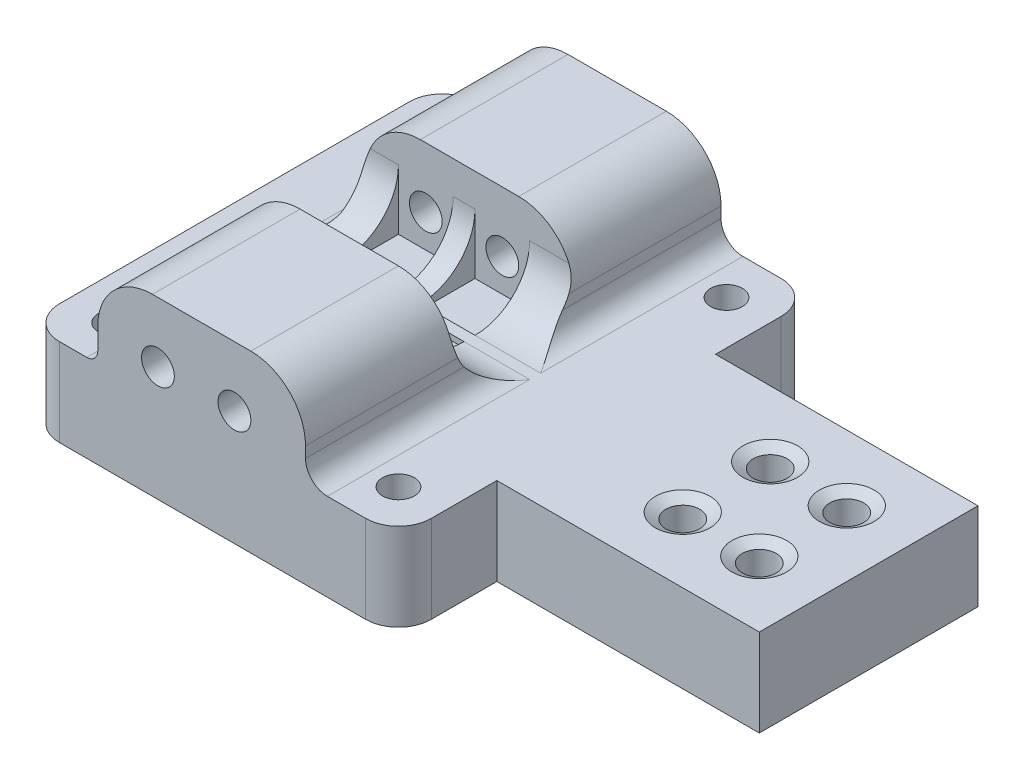
SolidWorks part; units mm, degrees
ref_plane "Front" through (0, 0, 0) normal (0, 0, 1) x (1, 0, 0)
ref_plane "Top" through (0, 0, 0) normal (0, 1, 0) x (1, 0, 0)
ref_plane "Right" through (0, 0, 0) normal (1, 0, 0) x (0, 0, -1)
sketch "Sketch1" plane through (0, 0, 0) normal (0, 1, 0) x (1, 0, 0)
  line L1 (0, 0) -> (300, 0)
  line L2 (0, 0) -> (0, -20)
  line L3 (0, -20) -> (300, -20)
  line L4 (300, 0) -> (300, -20)
  dimension "D1" = 20
  dimension "D2" = 300
extrude "Boss-Extrude1" add sketch "Sketch1" along normal blind 8
sketch "Sketch2" plane through (0, 0, 20) normal (0, 0, 1) x (1, 0, 0)
  line L0 (0, 8) -> (300, 8) construction
  line L1 (0, 0) -> (34, 0)
  line L2 (0, 0) -> (0, 8)
  line L3 (0, 8) -> (34, 8)
  line L4 (34, 0) -> (34, 8)
  line L5 (266, 8) -> (300, 8)
  line L6 (300, 0) -> (300, 8)
  line L7 (266, 0) -> (300, 0)
  line L8 (266, 0) -> (266, 8)
  dimension "D1" = 34
  dimension "D2" = 2
extrude "Boss-Extrude2" add sketch "Sketch2" along normal blind 9
sketch "Sketch3" plane through (0, 0, 0) normal (0, 0, -1) x (-1, 0, 0)
  line L0 (-300, 8) -> (0, 8) construction
  line L1 (0, 0) -> (-34, 0)
  line L2 (0, 0) -> (0, 8)
  line L3 (0, 8) -> (-34, 8)
  line L4 (-34, 0) -> (-34, 8)
  line L5 (-300, 0) -> (-300, 8)
  line L6 (-266, 8) -> (-300, 8)
  line L7 (-266, 0) -> (-266, 8)
  line L8 (-266, 0) -> (-300, 0)
  dimension "D1" = 34
  dimension "D2" = 2
extrude "Boss-Extrude3" add sketch "Sketch3" along normal blind 9
sketch "Sketch4" plane through (0, 8, 0) normal (0, 1, 0) x (1, 0, 0)
  line L0 (0, 9) -> (34, 9) construction
  line L1 (0, 9) -> (0, -29) construction
  circle A0 centre (4, 5) radius 1.45
  circle A1 centre (30, 5) radius 1.45
  circle A2 centre (30, -25) radius 1.45
  circle A3 centre (4, -25) radius 1.45
  circle A4 centre (296, -25) radius 1.45
  circle A5 centre (296, 5) radius 1.45
  circle A6 centre (270, -25) radius 1.45
  circle A7 centre (270, 5) radius 1.45
  dimension "D1" = 2.9
  dimension "D2" = 4
  dimension "D3" = 4
  dimension "D4" = 2
  dimension "D5" = 2
  dimension "D6" = 2
extrude "Cut-Extrude1" cut sketch "Sketch4" against normal through all
sketch "Sketch5" plane through (0, 0, 20) normal (0, 0, 1) x (1, 0, 0)
  line L0 (34, 8) -> (266, 8) construction
  line L1 (266, 0) -> (241, 0)
  line L2 (266, 0) -> (266, 8)
  line L3 (266, 8) -> (241, 8)
  line L4 (241, 0) -> (241, 8)
  dimension "D1" = 25
extrude "Boss-Extrude4" add sketch "Sketch5" along normal blind 17
sketch "Sketch6" plane through (0, 0, 0) normal (0, 0, -1) x (-1, 0, 0)
  line L0 (-266, 0) -> (-34, 0) construction
  line L1 (-266, 8) -> (-241, 8)
  line L2 (-266, 8) -> (-266, 0)
  line L3 (-266, 0) -> (-241, 0)
  line L4 (-241, 8) -> (-241, 0)
  dimension "D1" = 25
extrude "Boss-Extrude5" add sketch "Sketch6" along normal blind 17
sketch "Sketch12" plane through (0, 0, 37) normal (0, 0, 1) x (1, 0, 0)
  line L0 (241, 0) -> (266, 0) construction
  line L1 (241, 8) -> (249, 8)
  line L2 (241, 8) -> (241, 0)
  line L3 (241, 0) -> (249, 0)
  line L4 (249, 8) -> (249, 0)
  dimension "D1" = 8
extrude "Boss-Extrude7" add sketch "Sketch12" along normal blind 17
sketch "Sketch14" plane through (0, 0, 29) normal (0, 0, 1) x (1, 0, 0)
  line L0 (300, 8) -> (266, 8) construction
  line L1 (294.975, 8) -> (275, 8)
  line L2 (294.975, 8) -> (294.975, -5)
  line L3 (294.975, -5) -> (275, -4)
  line L4 (275, 8) -> (275, -4)
  line L7 (266, 8) -> (266, 0) construction
  dimension "D1" = 20
  dimension "D2" = 9
  dimension "D3" = 13
  dimension "D4" = 12
extrude "Boss-Extrude8" add sketch "Sketch14" along normal blind 12
sketch "Sketch15" plane through (294.975, 0, 0) normal (1, 0, 0) x (0, 0, -1)
  line L0 (-41, -5) -> (-41, 8) construction
  line L2 (-41, -5) -> (-29, -5) construction
  circle A0 centre (-35, 0) radius 1.6
  dimension "D1" = 3.2
  dimension "D2" = 6
  dimension "D3" = 5
extrude "Cut-Extrude7" cut sketch "Sketch15" against normal blind 20
sketch "Sketch16" plane through (0, 0, -9) normal (0, 0, -1) x (-1, 0, 0)
  line L0 (-266, 8) -> (-300, 8) construction
  line L1 (-295, 8) -> (-275, 8)
  line L2 (-295, 8) -> (-295, -5)
  line L3 (-295, -5) -> (-275, -5)
  line L4 (-275, 8) -> (-275, -5)
  line L6 (-266, 0) -> (-266, 8) construction
  dimension "D1" = 20
  dimension "D2" = 9
  dimension "D3" = 13
extrude "Boss-Extrude9" add sketch "Sketch16" along normal blind 12
sketch "Sketch17" plane through (295, 0, 0) normal (1, 0, 0) x (0, 0, -1)
  line L0 (21, -5) -> (9, -5) construction
  line L1 (21, 8) -> (21, -5) construction
  circle A0 centre (15, 0) radius 1.6
  dimension "D1" = 3.2
  dimension "D2" = 5
  dimension "D3" = 6
extrude "Cut-Extrude8" cut sketch "Sketch17" against normal blind 20
sketch "Sketch22" plane through (0, 8, 0) normal (0, 1, 0) x (1, 0, 0)
  line L0 (241, 17) -> (241, 0) construction
  line L1 (259, 9) -> (249, 9)
  line L2 (259, 9) -> (259, -29)
  line L3 (259, -29) -> (249, -29)
  line L4 (249, 9) -> (249, -29)
  line L5 (241, 17) -> (266, 17) construction
  line L6 (266, -37) -> (249, -37) construction
  dimension "D1" = 8
  dimension "D2" = 10
  dimension "D3" = 8
  dimension "D4" = 8
extrude "Cut-Extrude11" cut sketch "Sketch22" against normal through all
sketch "Sketch23" plane through (0, 0, 0) normal (0, -1, 0) x (-1, 0, 0)
  line L0 (-259, -29) -> (-259, 9) construction
  line L1 (-259, -19) -> (-267, -19)
  line L2 (-259, -19) -> (-259, -1)
  line L3 (-259, -1) -> (-267, -1)
  line L4 (-267, -19) -> (-267, -1)
  line L5 (-249, -29) -> (-259, -29) construction
  dimension "D1" = 8
  dimension "D2" = 10
  dimension "D3" = 10
extrude "Cut-Extrude12" cut sketch "Sketch23" against normal blind 4
sketch "Sketch24" plane through (259, 0, 0) normal (-1, 0, 0) x (0, 0, 1)
  line L0 (-9, 0) -> (-9, 8)
  line L1 (-9, 8) -> (-1, 8)
  line L2 (29, 8) -> (-9, 8) construction
  line L3 (-1, 8) -> (-9, 0)
  line L4 (29, 0) -> (29, 8)
  line L5 (29, 8) -> (21, 8)
  line L6 (21, 8) -> (29, 0)
  dimension "D1" = 8
  dimension "D2" = 8
extrude "Boss-Extrude12" add sketch "Sketch24" along normal blind 10
sketch "Sketch25" plane through (267, 0, 0) normal (-1, 0, 0) x (0, 0, 1)
  line L0 (19, 0) -> (19, 4)
  line L1 (19, 4) -> (15, 4)
  line L2 (1, 4) -> (19, 4) construction
  line L3 (15, 4) -> (19, 0)
  line L4 (1, 4) -> (5, 4)
  line L5 (5, 4) -> (1, 0)
  line L6 (1, 0) -> (1, 4)
  dimension "D1" = 4
  dimension "D2" = 4
extrude "Boss-Extrude13" add sketch "Sketch25" along normal blind 8
sketch "Sketch26" plane through (0, 8, 0) normal (0, 1, 0) x (1, 0, 0)
  line L0 (249, 1) -> (249, -21) construction
  line L1 (241, -54) -> (249, -54)
  line L2 (241, -54) -> (241, -6)
  line L3 (241, -6) -> (249, -6)
  line L4 (249, -54) -> (249, -6)
  dimension "D1" = 48
extrude "Boss-Extrude14" add sketch "Sketch26" along normal blind 14
sketch "Sketch27" plane through (0, 8, 0) normal (0, 1, 0) x (1, 0, 0)
  line L0 (249, -21) -> (259, -21) construction
  line L1 (249, -37) -> (257, -37)
  line L2 (249, -37) -> (249, -21)
  line L3 (249, -21) -> (257, -21)
  line L4 (257, -37) -> (257, -21)
  dimension "D1" = 8
extrude "Boss-Extrude15" add sketch "Sketch27" along normal blind 14
sketch "Sketch28" plane through (0, 0, 0) normal (0, -1, 0) x (1, 0, 0)
  line L0 (249, -9) -> (249, 29) construction
  line L1 (241, 54) -> (249, 54)
  line L2 (241, 54) -> (241, 14)
  line L3 (241, 14) -> (249, 14)
  line L4 (249, 54) -> (249, 14)
  dimension "D1" = 40
extrude "Cut-Extrude13" cut sketch "Sketch28" against normal blind 14
sketch "Sketch30" plane through (257, 0, 0) normal (1, 0, 0) x (0, 0, -1)
  line L0 (-37, 22) -> (-21, 22) construction
  line L1 (-21, 22) -> (-37, 22)
  line L2 (-21, 22) -> (-21, 8)
  line L3 (-21, 8) -> (-37, 8)
  line L4 (-37, 22) -> (-37, 8)
extrude "Boss-Extrude16" add sketch "Sketch30" along normal blind 9
sketch "Sketch31" plane through (0, 0, 0) normal (0, -1, 0) x (-1, 0, 0)
  line L1 (-249, -37) -> (-266, -37)
  line L2 (-249, -37) -> (-249, -29)
  line L3 (-249, -29) -> (-266, -29)
  line L4 (-266, -37) -> (-266, -29)
extrude "Cut-Extrude14" cut sketch "Sketch31" against normal blind 5
sketch "Sketch32" plane through (266, 0, 0) normal (1, 0, 0) x (0, 0, -1)
  line L0 (-37, 5) -> (-37, 22) construction
  line L1 (-21, 22) -> (-37, 22)
  line L2 (-21, 22) -> (-21, 13)
  line L3 (-21, 13) -> (-37, 13)
  line L4 (-37, 22) -> (-37, 13)
  dimension "D1" = 9
extrude "Cut-Extrude15" cut sketch "Sketch32" against normal blind 9
sketch "Sketch33" plane through (249, 0, 0) normal (-1, 0, 0) x (0, 0, 1)
  line L0 (29, 5) -> (24, 5)
  line L1 (21, 8) -> (29, 0) construction
  line L2 (24, 5) -> (29, 0)
  line L3 (29, 0) -> (29, 5)
extrude "Cut-Extrude16" cut sketch "Sketch33" against normal blind 10
sketch "Sketch34" plane through (0, 0, 29) normal (0, 0, 1) x (1, 0, 0)
  line L1 (266, 5) -> (259, 5)
  line L2 (266, 5) -> (266, 0)
  line L3 (266, 0) -> (259, 0)
  line L4 (259, 5) -> (259, 0)
extrude "Cut-Extrude17" cut sketch "Sketch34" against normal blind 5
sketch "Sketch35" plane through (0, 0, 21) normal (0, 0, -1) x (-1, 0, 0)
  line L0 (-249, 8) -> (-259, 8) construction
  line L1 (-259, 8) -> (-266, 8)
  line L2 (-259, 8) -> (-259, 13)
  line L3 (-259, 13) -> (-266, 13)
  line L4 (-266, 8) -> (-266, 13)
  line L5 (-266, 8) -> (-259, 8) construction
  line L6 (-266, 8) -> (-266, 13) construction
extrude "Boss-Extrude17" add sketch "Sketch35" along normal blind 5
sketch "Sketch36" plane through (0, 22, 0) normal (0, 1, 0) x (1, 0, 0)
  line L0 (241, -54) -> (249, -54) construction
  line L1 (249, -54) -> (249, -37) construction
  circle A0 centre (245, -50) radius 1.7
  circle A1 centre (245, -18) radius 1.7
  dimension "D1" = 3.4
  dimension "D2" = 4
  dimension "D3" = 4
  dimension "D4" = 2
extrude "Cut-Extrude18" cut sketch "Sketch36" against normal through all
sketch "Sketch37" plane through (0, 8, 0) normal (0, 1, 0) x (1, 0, 0)
  line L0 (241, -6) -> (171, -6)
  line L1 (241, -6) -> (241, -14) construction
  line L2 (241, -6) -> (241, -14)
  line L3 (241, -14) -> (241, -20) construction
  line L4 (241, -14) -> (171, -14)
  line L5 (171, -14) -> (171, -6)
  dimension "D1" = 70
extrude "Boss-Extrude18" add sketch "Sketch37" along normal blind 5
sketch "Sketch39" plane through (0, 8, 0) normal (0, 1, 0) x (1, 0, 0)
  line L0 (34, -20) -> (241, -20) construction
  line L1 (241, -14) -> (175, -14)
  line L2 (241, -14) -> (241, -20)
  line L3 (241, -20) -> (175, -20)
  line L4 (175, -14) -> (175, -20)
  dimension "D1" = 66
extrude "Cut-Extrude19" cut sketch "Sketch39" against normal through all
sketch "Sketch46" plane through (0, 8, 0) normal (0, 1, 0) x (1, 0, 0)
  line L1 (295, 9) -> (275, 9)
  line L2 (295, 9) -> (295, 21)
  line L3 (295, 21) -> (275, 21)
  line L4 (275, 9) -> (275, 21)
  line L5 (294.975, -41) -> (275, -41)
  line L6 (294.975, -41) -> (294.975, -29)
  line L7 (294.975, -29) -> (275, -29)
  line L8 (275, -41) -> (275, -29)
extrude "Boss-Extrude23" add sketch "Sketch46" along normal blind 10
sketch "Sketch47" plane through (0, 18, 0) normal (0, 1, 0) x (1, 0, 0)
  line L0 (295, 21) -> (275, 21) construction
  line L1 (275, 21) -> (303, 21)
  line L2 (275, 21) -> (275, 9)
  line L3 (275, 9) -> (303, 9)
  line L4 (303, 21) -> (303, 9)
  line L5 (275, 9) -> (295, 9) construction
  line L6 (294.975, -29) -> (275, -29) construction
  line L7 (274.975, -29) -> (303, -29)
  line L8 (274.975, -29) -> (274.975, -41)
  line L9 (274.975, -41) -> (303, -41)
  line L10 (303, -29) -> (303, -41)
  line L11 (275, -41) -> (294.975, -41) construction
  line L12 (275, 21) -> (275, 9) construction
  line L13 (295, 9) -> (295, 21) construction
  line L14 (275, -29) -> (275, -41) construction
  line L15 (294.975, -41) -> (294.975, -29) construction
  dimension "D1" = 28
  dimension "D2" = 20
  dimension "D3" = 28
  dimension "D4" = 20
extrude "Boss-Extrude24" add sketch "Sketch47" along normal blind 5 and the other way blind 5
sketch "Sketch48" plane through (303, 0, 0) normal (1, 0, 0) x (0, 0, -1)
  line L2 (-41, 13) -> (-41, 23) construction
  line L3 (21, 13) -> (21, 23) construction
  line L4 (9, 23) -> (21, 23) construction
  line L5 (-41, 23) -> (-29, 23) construction
  circle A0 centre (16, 18) radius 1.5
  circle A1 centre (-36, 18) radius 1.5
  dimension "D1" = 3
  dimension "D2" = 3
  dimension "D3" = 5
  dimension "D4" = 5
  dimension "D5" = 5
  dimension "D6" = 5
extrude "Cut-Extrude22" cut sketch "Sketch48" against normal blind 15
sketch "Sketch49" plane through (0, 8, 0) normal (0, 1, 0) x (1, 0, 0)
  line L0 (241, 0) -> (34, 0) construction
  line L1 (34, -20) -> (175, -20) construction
  line L2 (0, 9) -> (0, -29) construction
  circle A0 centre (78, -8) radius 1.45
  circle A1 centre (78, -12) radius 1.45
  dimension "D1" = 2.9
  dimension "D2" = 2.9
  dimension "D3" = 8
  dimension "D4" = 8
  dimension "D5" = 78
  dimension "D6" = 78
extrude "Cut-Extrude23" cut sketch "Sketch49" against normal through all
sketch "Sketch50" plane through (303, 0, 0) normal (1, 0, 0) x (0, 0, -1)
  line L1 (28.7085, 47.789) -> (-67.8332, 47.789)
  line L2 (28.7085, 47.789) -> (28.7085, -51.3705)
  line L3 (28.7085, -51.3705) -> (-67.8332, -51.3705)
  line L4 (-67.8332, 47.789) -> (-67.8332, -51.3705)
extrude "Cut-Extrude24" cut sketch "Sketch50" against normal blind 245
sketch "Sketch51" plane through (0, 8, 0) normal (0, 1, 0) x (1, 0, 0)
  line L1 (34, -20) -> (58, -20) construction
  line L2 (58, 0) -> (34, 0) construction
  line L4 (58, 0) -> (58, -20) construction
  circle A0 centre (52, -14) radius 1.55
  circle A1 centre (45, -14) radius 1.55
  circle A2 centre (45, -6) radius 1.55
  circle A3 centre (52, -6) radius 1.55
  dimension "D1" = 3.1
  dimension "D2" = 3.1
  dimension "D3" = 3.1
  dimension "D4" = 3.1
  dimension "D5" = 6
  dimension "D6" = 6
  dimension "D7" = 6
  dimension "D8" = 6
  dimension "D9" = 7
  dimension "D10" = 7
extrude "Cut-Extrude25" cut sketch "Sketch51" against normal through all
sketch "Sketch52" plane through (0, 8, 0) normal (0, 1, 0) x (1, 0, 0)
  line L0 (0, 9) -> (34, 9) construction
  line L1 (25.5, 9) -> (6.5, 9)
  line L2 (25.5, 9) -> (25.5, -4.5)
  line L3 (25.5, -4.5) -> (6.5, -4.5)
  line L4 (6.5, 9) -> (6.5, -4.5)
  line L5 (34, -29) -> (0, -29) construction
  line L6 (25.5, -29) -> (6.5, -29)
  line L7 (25.5, -29) -> (25.5, -15.5)
  line L8 (25.5, -15.5) -> (6.5, -15.5)
  line L9 (6.5, -29) -> (6.5, -15.5)
  line L10 (0, 9) -> (0, -29) construction
  dimension "D1" = 13.5
  dimension "D2" = 13.5
  dimension "D3" = 19
  dimension "D4" = 19
  dimension "D5" = 6.5
  dimension "D6" = 6.5
extrude "Boss-Extrude25" add sketch "Sketch52" along normal blind 8
fillet "Fillet1" radius 5 2 edges at (16, 8, 4.5) (16, 8, 15.5)
sketch "Sketch53" plane through (0, 0, -9) normal (0, 0, -1) x (-1, 0, 0)
  line L0 (-25.5, 16) -> (-6.5, 16) construction
  line L1 (-6.5, 16) -> (-6.5, 8) construction
  line L2 (-25.5, 16) -> (-25.5, 8) construction
  circle A0 centre (-19, 10.5) radius 1.5
  circle A1 centre (-12, 10.5) radius 1.5
  dimension "D1" = 3
  dimension "D2" = 3
  dimension "D3" = 5.5
  dimension "D4" = 5.5
  dimension "D5" = 5.5
  dimension "D6" = 6.5
extrude "Cut-Extrude26" cut sketch "Sketch53" against normal through all
fillet "Fillet2" radius 5 4 edges at (25.5, 16, 22.25) (6.5, 16, 22.25) (6.5, 16, -2.25) (25.5, 16, -2.25)
fillet "Fillet3" radius 3 4 edges at (34, 4, 29) (0, 4, 29) (0, 4, -9) (34, 4, -9)
sketch "Sketch54" plane through (0, 16, 0) normal (0, 1, 0) x (1, 0, 0)
  line L0 (11.5, -4.5) -> (20.5, -4.5) construction
  line L1 (16.5, -4.5) -> (21.5, -4.5)
  line L2 (16.5, -4.5) -> (16.5, -9.5)
  line L3 (16.5, -9.5) -> (21.5, -9.5)
  line L4 (21.5, -4.5) -> (21.5, -9.5)
  line L5 (20.5, -15.5) -> (11.5, -15.5) construction
  line L6 (14.5, -4.5) -> (9.5, -4.5)
  line L7 (14.5, -4.5) -> (14.5, -9.5)
  line L8 (14.5, -9.5) -> (9.5, -9.5)
  line L9 (9.5, -4.5) -> (9.5, -9.5)
  line L10 (16.5, -15.5) -> (21.5, -15.5)
  line L11 (16.5, -15.5) -> (16.5, -10.5)
  line L12 (16.5, -10.5) -> (21.5, -10.5)
  line L13 (21.5, -15.5) -> (21.5, -10.5)
  line L14 (11.5, 9) -> (11.5, -4.5) construction
  line L15 (14.5, -15.5) -> (9.5, -15.5)
  line L16 (14.5, -15.5) -> (14.5, -10.5)
  line L17 (14.5, -10.5) -> (9.5, -10.5)
  line L18 (9.5, -15.5) -> (9.5, -10.5)
  line L19 (20.5, -4.5) -> (20.5, 9) construction
  line L20 (11.5, -15.5) -> (11.5, -29) construction
  line L21 (20.5, -29) -> (20.5, -15.5) construction
  dimension "D1" = 5
  dimension "D2" = 5
  dimension "D3" = 5
  dimension "D4" = 5
  dimension "D5" = 3
  dimension "D6" = 4
  dimension "D7" = 5
  dimension "D8" = 5
  dimension "D9" = 5
  dimension "D10" = 5
  dimension "D11" = 3
  dimension "D12" = 4
extrude "Cut-Extrude27" cut sketch "Sketch54" against normal blind 8.5
fillet "Fillet4" radius 1 2 edges at (6.5, 8, 19.75) (6.5, 8, 0.25)
fillet "Fillet5" radius 2 2 edges at (25.5, 8, 19.75) (25.5, 8, 0.25)
sketch "Sketch55" plane through (0, 8, 0) normal (0, 1, 0) x (1, 0, 0)
  circle A0 centre (45, -6) radius 2.5
  circle A1 centre (52, -6) radius 2.5
  circle A2 centre (52, -14) radius 2.5
  circle A3 centre (45, -14) radius 2.5
  dimension "D1" = 5
  dimension "D2" = 5
  dimension "D3" = 5
  dimension "D4" = 5
extrude "Cut-Extrude28" cut sketch "Sketch55" against normal blind 2 draft 60
